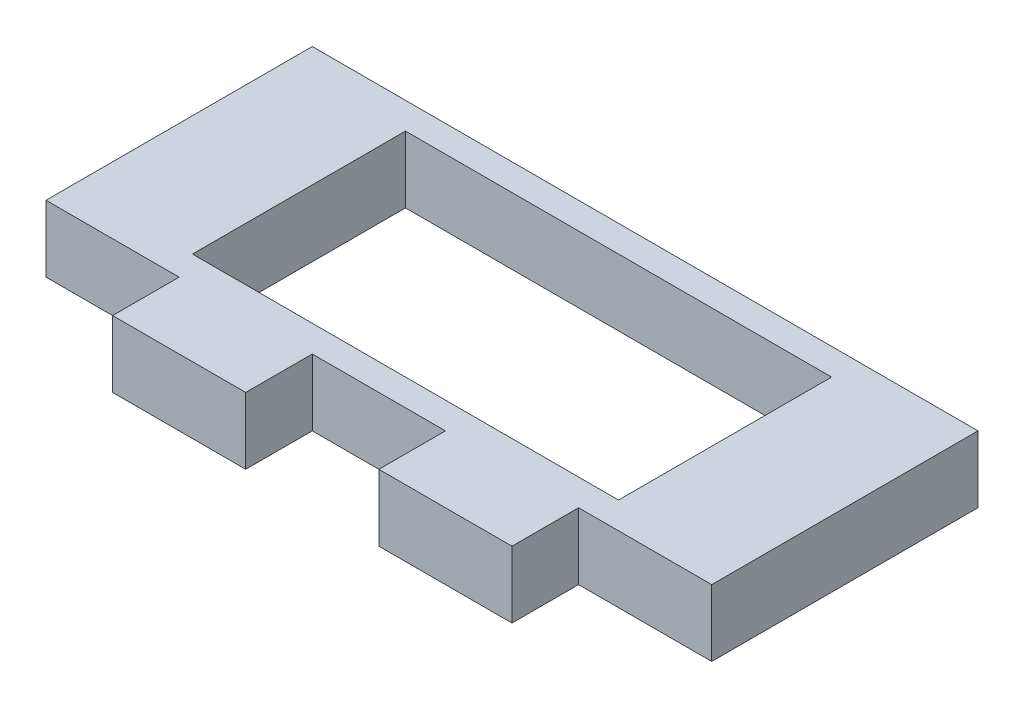
SolidWorks part; units mm, degrees
ref_plane "Front Plane" through (0, 0, 0) normal (0, 0, 1) x (1, 0, 0)
ref_plane "Top Plane" through (0, 0, 0) normal (0, 1, 0) x (1, 0, 0)
ref_plane "Right Plane" through (0, 0, 0) normal (1, 0, 0) x (0, 0, -1)
sketch "Sketch1" plane through (0, 0, 0) normal (0, 1, 0) x (1, 0, 0)
  line L0 (0, 0) -> (0, 13.5231) construction
  line L1 (-31.75, 12.7) -> (31.75, 12.7)
  line L2 (-31.75, 12.7) -> (-31.75, -12.7)
  line L3 (-31.75, -12.7) -> (-19.05, -12.7)
  line L4 (31.75, 12.7) -> (31.75, -12.7)
  line L5 (0, 0) -> (26.1056, 0) construction
  line L6 (-6.35, -12.7) -> (6.35, -12.7)
  line L7 (19.05, -12.7) -> (31.75, -12.7)
  line L8 (-19.05, -12.7) -> (-19.05, -19.05)
  line L9 (-19.05, -19.05) -> (-6.35, -19.05)
  line L10 (-6.35, -12.7) -> (-6.35, -19.05)
  line L12 (6.35, -12.7) -> (6.35, -19.05)
  line L13 (6.35, -19.05) -> (19.05, -19.05)
  line L14 (19.05, -12.7) -> (19.05, -19.05)
  line L15 (-20.32, 10.16) -> (20.32, 10.16)
  line L16 (-20.32, 10.16) -> (-20.32, -10.16)
  line L17 (-20.32, -10.16) -> (20.32, -10.16)
  line L18 (20.32, 10.16) -> (20.32, -10.16)
  dimension "D1" = 6.35
  dimension "D2" = 6.35
  dimension "D3" = 12.7
  dimension "D4" = 12.7
  dimension "D5" = 12.7
  dimension "D6" = 63.5
  dimension "D7" = 25.4
  dimension "D8" = 20.32
  dimension "D9" = 40.64
extrude "Boss-Extrude1" add sketch "Sketch1" along normal blind 6.35
